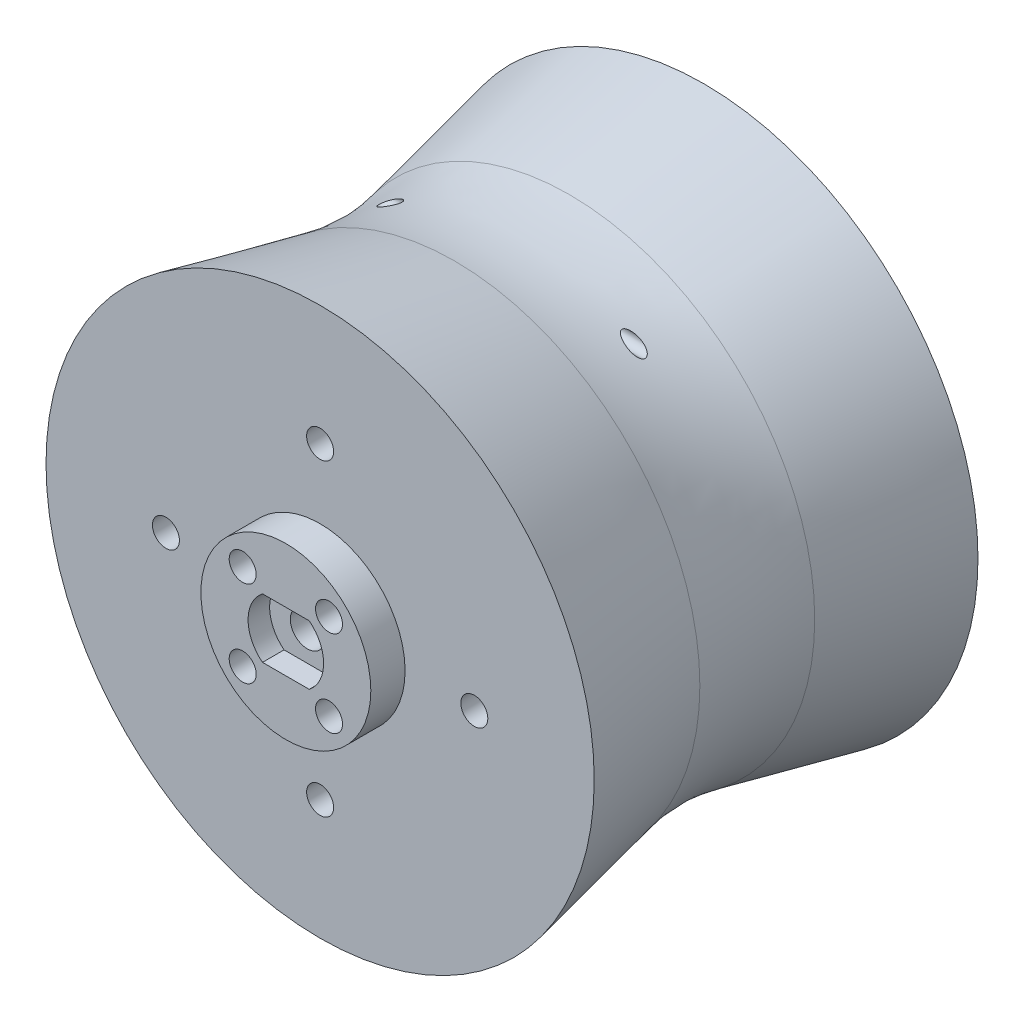
SolidWorks part; units mm, degrees
ref_plane "Front Plane" through (0, 0, 0) normal (0, 0, 1) x (1, 0, 0)
ref_plane "Top Plane" through (0, 0, 0) normal (0, 1, 0) x (1, 0, 0)
ref_plane "Right Plane" through (0, 0, 0) normal (1, 0, 0) x (0, 0, -1)
sketch "Sketch1" plane through (0, 0, 0) normal (0, 0, 1) x (1, 0, 0)
  circle A0 centre (0, 0) radius 50.8
  circle A1 centre (0, 0) radius 3.175
  dimension "D1" = 101.6
  dimension "D2" = 6.35
extrude "Boss-Extrude1" add sketch "Sketch1" along normal blind 71.12
sketch "Sketch2" plane through (0, 0, 0) normal (1, 0, 0) x (0, 0, -1)
  line L1 (39.116, 0) -> (-39.116, 0) construction
  line L2 (0, 55.88) -> (0, -55.88) construction
  circle A0 centre (-35.56, 38.1) radius 1.27
  dimension "D1" = 2.54
  dimension "D2" = 38.1
  dimension "D3" = 35.56
extrude "Cut-Extrude1" cut sketch "Sketch2" against normal through all both and the other way through all
sketch "Sketch7" plane through (0, 0, 0) normal (0, 0, -1) x (-1, 0, 0)
  line L0 (0, 28.575) -> (0, -28.575) construction
  line L1 (0, 42.6085) -> (0, -42.6085) construction
  line L2 (0, 28.575) -> (0, -28.575) construction
  line L3 (-28.575, 0) -> (28.575, 0) construction
  line L4 (42.6085, 0) -> (-42.6085, 0) construction
  line L5 (28.575, 0) -> (-28.575, 0) construction
  circle A0 centre (28.575, 0) radius 2.5
  circle A1 centre (0, 28.575) radius 2.5
  circle A2 centre (-28.575, 0) radius 2.5
  circle A3 centre (0, -28.575) radius 2.5
  point P7 (0, 0)
  point P14 (0, 0)
  dimension "D1" = 5
  dimension "D2" = 57.15
extrude "Cut-Extrude4" cut sketch "Sketch7" against normal blind 12.7
ref_plane "Plane1" through (0, 0, 35.56) normal (0, 0, 1) x (1, 0, 0)
mirror "Mirror1" about plane through (0, 0, 35.56) normal (0, 0, 1) of "Cut-Extrude4"
sketch "Sketch8" plane through (0, 0, 71.12) normal (0, 0, 1) x (1, 0, 0)
  circle A0 centre (0, 0) radius 15.748
  circle A1 centre (0, 0) radius 3.175 construction
  circle A2 centre (0, 0) radius 3.175
  dimension "D1" = 31.496
extrude "Boss-Extrude2" add sketch "Sketch8" along normal blind 6.35
sketch "Sketch5" plane through (0, 0, 77.47) normal (0, 0, 1) x (1, 0, 0)
  line L0 (-4.3301, 5.5) -> (4.3301, 5.5)
  line L1 (4.3301, -5.5) -> (-4.3301, -5.5)
  arc A0 (-4.3301, 5.5) -> (-4.3301, -5.5) centre (0, 0) ccw
  arc A1 (4.3301, -5.5) -> (4.3301, 5.5) centre (0, 0) ccw
  dimension "D1" = 14
  dimension "D2" = 5.5
  dimension "D3" = 11
sketch "Sketch6" plane through (0, 0, 77.47) normal (0, 0, 1) x (1, 0, 0)
  line L0 (0, 8) -> (0, -8) construction
  line L1 (-8, -8) -> (8, -8) construction
  line L3 (-8, 8) -> (8, 8) construction
  circle A4 centre (-8, 8) radius 2.5
  circle A6 centre (8, 8) radius 2.5
  circle A7 centre (8, -8) radius 2.5
  circle A9 centre (-8, -8) radius 2.5
  point P3 (0, 0)
  point P6 (0, -8)
  point P9 (0, 8)
  dimension "D1" = 5
  dimension "D2" = 16
  dimension "D3" = 16
extrude "Cut-Extrude6" cut sketch "Sketch5" against normal blind 4
extrude "Cut-Extrude7" cut sketch "Sketch6" against normal blind 7
ref_axis "Axis1" through (0, 0, -3.8735) along (0, 0, 1)
sketch "Sketch9" plane through (0, 0, 0) normal (1, 0, 0) x (0, 0, -1)
  line L0 (-71.12, 50.8) -> (-46.2041, 45.4609)
  line L1 (-24.9159, 45.4609) -> (0, 50.8)
  line L2 (0, 50.8) -> (-71.12, 50.8)
  line L3 (-35.56, 50.8) -> (-35.56, 43.18) construction
  line L4 (0, -50.8) -> (0, 50.8) construction
  arc A0 (-46.2041, 45.4609) -> (-24.9159, 45.4609) centre (-35.56, 95.1332) ccw
  point P8 (0, 50.8)
  dimension "D2" = 50.8
  dimension "D1" = 7.62
revolve "Cut-Revolve1" cut sketch "Sketch9" angle 360 about axis through (0, 0, -3.8735) along (0, 0, 1)
